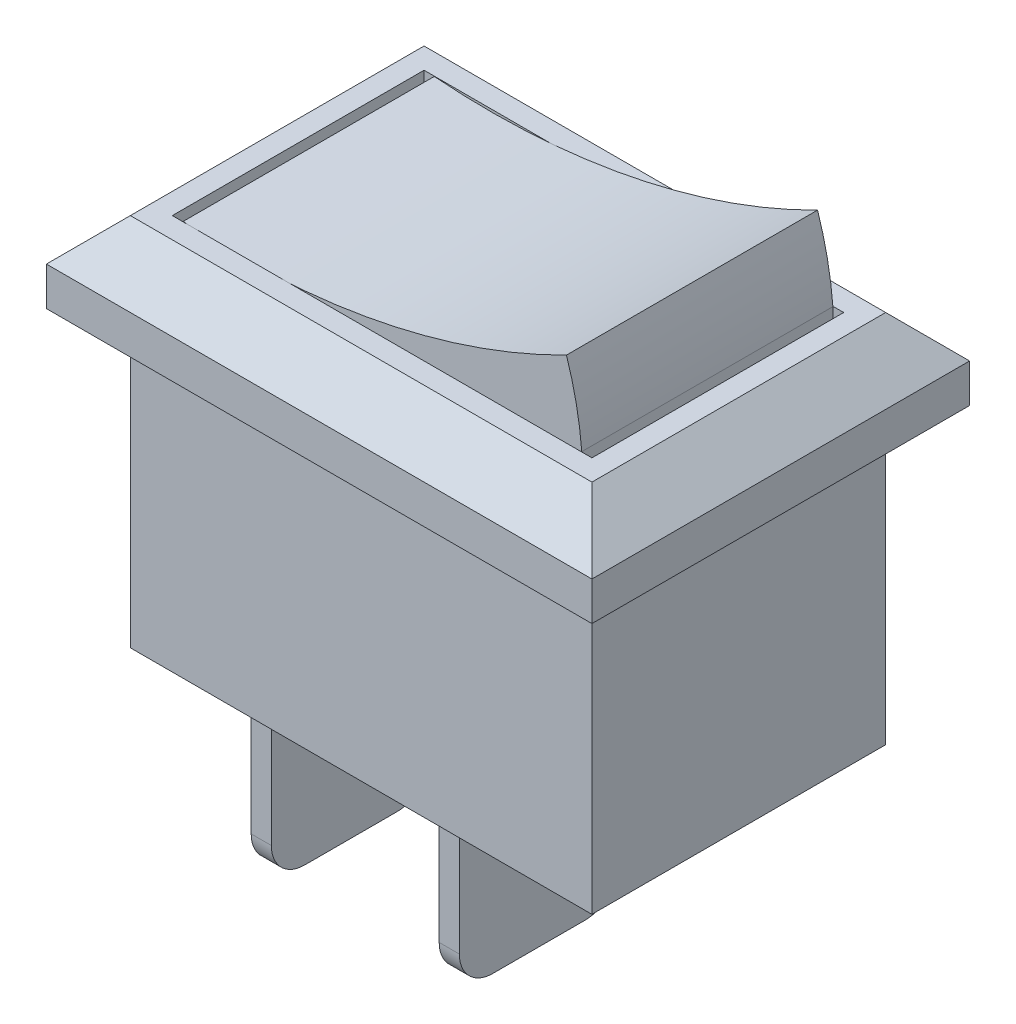
SolidWorks part; units mm, degrees
ref_plane "Front Plane" through (0, 0, 0) normal (0, 0, 1) x (1, 0, 0)
ref_plane "Top Plane" through (0, 0, 0) normal (0, 1, 0) x (1, 0, 0)
ref_plane "Right Plane" through (0, 0, 0) normal (1, 0, 0) x (0, 0, -1)
sketch "Sketch1" plane through (0, 0, 0) normal (0, 1, 0) x (1, 0, 0)
  line L1 (0, 0) -> (17.4625, 0)
  line L2 (0, 0) -> (0, 11.1125)
  line L3 (0, 11.1125) -> (17.4625, 11.1125)
  line L4 (17.4625, 0) -> (17.4625, 11.1125)
  dimension "D1" = 17.4625
  dimension "D2" = 11.1125
extrude "Boss-Extrude1" add sketch "Sketch1" along normal blind 11.1125
sketch "Sketch2" plane through (0, 11.1125, 0) normal (0, 1, 0) x (1, 0, 0)
  line L0 (0, 11.1125) -> (0, 0) construction
  line L1 (-1.5875, 12.7) -> (19.05, 12.7)
  line L2 (-1.5875, 12.7) -> (-1.5875, -1.5875)
  line L3 (-1.5875, -1.5875) -> (19.05, -1.5875)
  line L4 (19.05, 12.7) -> (19.05, -1.5875)
  line L5 (0, 0) -> (17.4625, 0) construction
  dimension "D1" = 20.6375
  dimension "D2" = 14.2875
  dimension "D3" = 1.5875
  dimension "D4" = 1.5875
extrude "Boss-Extrude2" add sketch "Sketch2" along normal blind 3.048
chamfer "Chamfer1" distance 1.5875 angle 45 4 edges at (8.7313, 14.1605, -12.7) (19.05, 14.1605, -5.5562) (8.7313, 14.1605, 1.5875) (-1.5875, 14.1605, -5.5562)
sketch "Sketch3" plane through (0, 14.1605, 0) normal (0, 1, 0) x (1, 0, 0)
  line L0 (0, 11.1125) -> (0, 0) construction
  line L1 (0.7937, 10.3188) -> (16.6688, 10.3188)
  line L2 (0.7937, 10.3188) -> (0.7937, 0.7937)
  line L3 (0.7937, 0.7937) -> (16.6688, 0.7937)
  line L4 (16.6688, 10.3188) -> (16.6688, 0.7937)
  line L5 (17.4625, 11.1125) -> (0, 11.1125) construction
  line L6 (17.4625, 0) -> (17.4625, 11.1125) construction
  line L7 (0, 0) -> (17.4625, 0) construction
  dimension "D1" = 0.7937
  dimension "D2" = 0.7937
  dimension "D3" = 0.7937
  dimension "D4" = 0.7937
extrude "Cut-Extrude1" cut sketch "Sketch3" against normal blind 3.175
ref_plane "Plane1" through (0, 0, -5.5562) normal (0, 0, 1) x (1, 0, 0)
sketch "Sketch4" plane through (0, 0, -5.5562) normal (0, 0, 1) x (1, 0, 0)
  line L0 (16.6688, 10.9855) -> (0.7937, 10.9855) construction
  line L1 (1.1906, 10.9855) -> (16.2719, 10.9855)
  line L2 (1.1906, 10.9855) -> (1.1906, 14.1605)
  line L4 (16.2719, 10.9855) -> (16.2719, 14.1605)
  line L7 (16.6688, 10.9855) -> (16.6688, 14.1605) construction
  line L8 (0.7937, 10.9855) -> (0.7937, 14.1605) construction
  arc A0 (1.1906, 14.1605) -> (15.6924, 17.033) centre (3.3227, 41.4384) ccw
  spline S0 degree 2 poles (16.2719, 14.1605) (16.1535, 15.6323) (15.6924, 17.033) knots 0 0 0 1 1 1
  dimension "D1" = 0.3969
  dimension "D2" = 0.3969
extrude "Boss-Extrude3" add sketch "Sketch4" along normal blind 4.7498 and the other way blind 4.7498
sketch "Sketch5" plane through (0, 0, 0) normal (0, -1, 0) x (1, 0, 0)
  line L0 (0, 0) -> (17.4625, 0) construction
  line L1 (2.032, -2.54) -> (2.794, -2.54)
  line L2 (2.032, -2.54) -> (2.032, -8.5725)
  line L3 (2.032, -8.5725) -> (2.794, -8.5725)
  line L4 (2.794, -2.54) -> (2.794, -8.5725)
  line L5 (9.144, -2.54) -> (9.906, -2.54)
  line L6 (9.144, -2.54) -> (9.144, -8.5725)
  line L7 (9.144, -8.5725) -> (9.906, -8.5725)
  line L8 (9.906, -2.54) -> (9.906, -8.5725)
  line L9 (17.4625, -11.1125) -> (0, -11.1125) construction
  line L10 (0, -11.1125) -> (0, 0) construction
  dimension "D1" = 2.54
  dimension "D2" = 2.54
  dimension "D3" = 0.762
  dimension "D4" = 0.762
  dimension "D5" = 2.032
  dimension "D6" = 6.35
extrude "Boss-Extrude4" add sketch "Sketch5" along normal blind 7.62
fillet "Fillet1" radius 1.27 4 edges at (9.525, -7.62, -8.5725) (9.525, -7.62, -2.54) (2.413, -7.62, -2.54) (2.413, -7.62, -8.5725)
